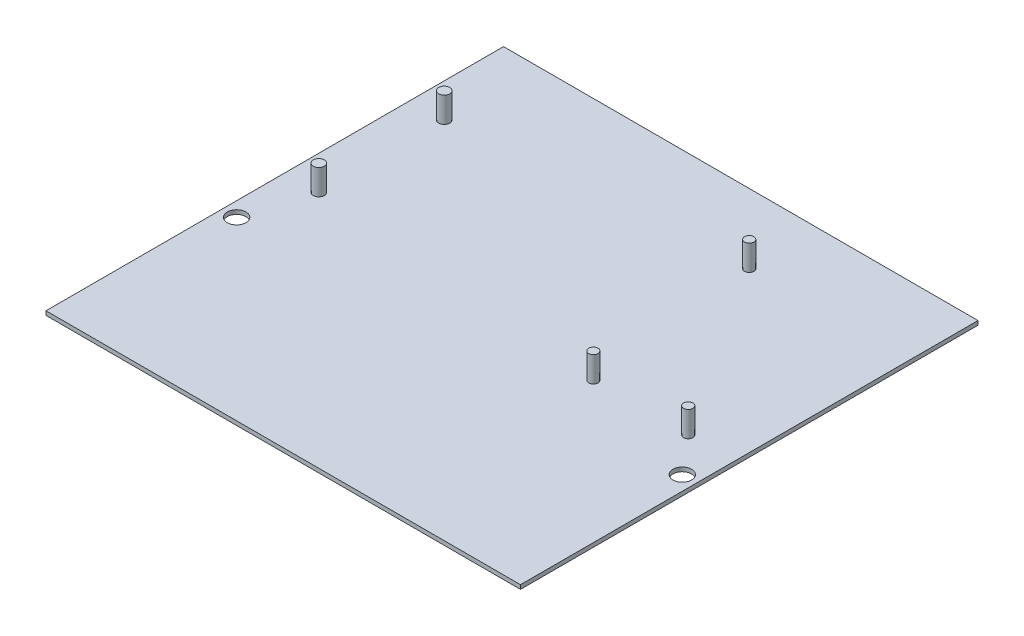
SolidWorks part; units mm, degrees
ref_plane "Front Plane" through (0, 0, 0) normal (0, 0, 1) x (1, 0, 0)
ref_plane "Top Plane" through (0, 0, 0) normal (0, 1, 0) x (1, 0, 0)
ref_plane "Right Plane" through (0, 0, 0) normal (1, 0, 0) x (0, 0, -1)
sketch "Sketch1" plane through (0, 0, 0) normal (0, 1, 0) x (1, 0, 0)
  line L1 (-70, 67.5) -> (70, 67.5)
  line L2 (-70, 67.5) -> (-70, -67.5)
  line L3 (-70, -67.5) -> (70, -67.5)
  line L4 (70, 67.5) -> (70, -67.5)
  line L5 (-70, 67.5) -> (70, -67.5) construction
  line L6 (-70, -67.5) -> (70, 67.5) construction
  point P0 (0, 0)
  dimension "D1" = 135
  dimension "D2" = 140
extrude "Boss-Extrude1" add sketch "Sketch1" along normal blind 1.2
sketch "Sketch2" plane through (0, 1.2, 0) normal (0, 1, 0) x (1, 0, 0)
  line L0 (0, 83.2384) -> (0, -101.5897) construction
  line L1 (70, 67.5) -> (-70, 67.5) construction
  circle A0 centre (65.75, -15.5) radius 2.75
  dimension "D1" = 5.5
  dimension "D2" = 65.75
  dimension "D3" = 83
extrude "Cut-Extrude1" cut sketch "Sketch2" against normal up to next
mirror "Mirror1" about plane through (0, 0, 0) normal (1, 0, 0) of "Cut-Extrude1"
sketch "Sketch3" plane through (0, 1.2, 0) normal (0, 1, 0) x (1, 0, 0)
  line L0 (-70, 67.5) -> (-70, -67.5) construction
  line L1 (70, 67.5) -> (-70, 67.5) construction
  circle A0 centre (-60, 40) radius 1.625
  circle A1 centre (-60, 3) radius 1.625
  dimension "D2" = 3.25
  dimension "D4" = 3.25
  dimension "D1" = 10
  dimension "D3" = 27.5
  dimension "D5" = 37
  dimension "D6" = 10
extrude "Boss-Extrude2" add sketch "Sketch3" along normal blind 7.5
sketch "Sketch4" plane through (0, 1.2, 0) normal (0, 1, 0) x (1, 0, 0)
  line L0 (70, -67.5) -> (70, 67.5) construction
  line L1 (63, -15.5) -> (68.5, -15.5) construction
  circle A0 centre (56.5, -4.5) radius 1.375
  circle A2 centre (65.75, -15.5) radius 2.75 construction
  circle A3 centre (28.5, -4.5) radius 1.375
  circle A4 centre (23, 47) radius 1.375
  dimension "D2" = 2.75
  dimension "D4" = 2.75
  dimension "D7" = 2.75
  dimension "D1" = 13.5
  dimension "D3" = 11
  dimension "D5" = 28
  dimension "D6" = 11
  dimension "D8" = 51.5
  dimension "D9" = 5.5
extrude "Boss-Extrude3" add sketch "Sketch4" along normal blind 7.5
